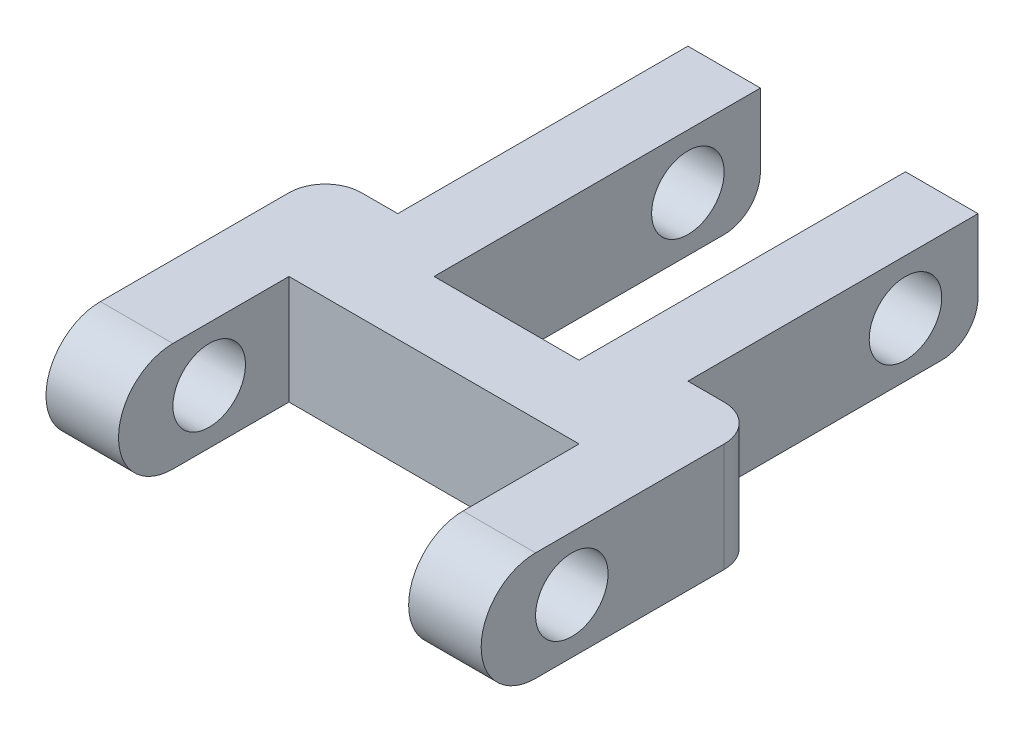
SolidWorks part; units mm, degrees
ref_plane "前视基准面" through (0, 0, 0) normal (0, 0, 1) x (1, 0, 0)
ref_plane "上视基准面" through (0, 0, 0) normal (0, 1, 0) x (1, 0, 0)
ref_plane "右视基准面" through (0, 0, 0) normal (1, 0, 0) x (0, 0, -1)
other "Configuration Table"
sketch "草图1" plane through (0, 0, 0) normal (0, 1, 0) x (1, 0, 0)
  line L0 (-6, 0) -> (6, 0)
  line L1 (-6, 0) -> (-6, -8.7)
  line L2 (-6, -8.7) -> (-4, -8.7)
  line L3 (-4, -8.7) -> (-4, -3)
  line L4 (-4, -3) -> (4, -3)
  line L5 (4, -3) -> (4, -8.7)
  line L6 (4, -8.7) -> (6, -8.7)
  line L7 (6, -8.7) -> (6, 0)
  point P4 (0, 0)
  dimension "D1" = 8.7
  dimension "D2" = 2
  dimension "D3" = 5.7
  dimension "D4" = 8
  dimension "D5" = 8.7
  dimension "D6" = 5.7
  dimension "D7" = 90
  dimension "D8" = 6
extrude "凸台-拉伸1" add sketch "草图1" along normal blind 3
sketch "草图2" plane through (-6, 0, 0) normal (-1, 0, 0) x (0, 0, 1)
  line L2 (6.2, 3) -> (0, 3)
  line L3 (0, 3) -> (0, 0)
  line L4 (0, 0) -> (6.2, 0)
  arc A0 (6.2, 0) -> (6.2, 3) centre (6.2, 1.5) ccw
  dimension "D2" = 6.2
  dimension "D1" = 1.5
  dimension "D3" = 1.5
  dimension "D4" = 6.2
  dimension "D5" = 1.5
extrude "切除-拉伸1" cut sketch "草图2" against normal blind 12 flip side to cut
sketch "草图3" plane through (-6, 0, 0) normal (-1, 0, 0) x (0, 0, 1)
  line L0 (6.2, 1.5) -> (5.2, 1.5) construction
  circle A2 centre (5.2, 1.5) radius 1
  dimension "D3" = 2
  dimension "D2" = 1
extrude "切除-拉伸2" cut sketch "草图3" against normal blind 12
fillet "圆角1" radius 1 2 edges at (6, 1.5, 0) (-6, 1.5, 0)
sketch "草图4" plane through (0, 0, 0) normal (0, 0, -1) x (-1, 0, 0)
  line L0 (0, 3) -> (0, 0) construction
  line L1 (-5, 3) -> (5, 3) construction
  circle A0 centre (0, 1.5) radius 0.95
  dimension "D1" = 1.9
extrude "凸台-拉伸2" add sketch "草图4" along normal blind 2
ref_plane "基准面1" through (0, 0, -2) normal (0, 0, -1) x (-1, 0, 0)
sketch "草图5" plane through (0, 0, -2) normal (0, 0, -1) x (-1, 0, 0)
  line L15 (-4, 3) -> (4, 3)
  line L16 (-5, 3) -> (5, 3) construction
  line L17 (4, 3) -> (4, 0)
  line L18 (-5, 0) -> (5, 0) construction
  line L19 (4, 0) -> (-4, 0)
  line L20 (-4, 0) -> (-4, 3)
  point P5 (0, 3)
  dimension "D1" = 3
  dimension "D2" = 8
extrude "凸台-拉伸3" add sketch "草图5" along normal blind 6
sketch "草图6" plane through (4, 0, 0) normal (1, 0, 0) x (0, 0, -1)
  line L0 (8, 1.5) -> (6, 1.5) construction
  line L1 (8, 3) -> (8, 0) construction
  circle A1 centre (6, 1.5) radius 1
  dimension "D3" = 2
  dimension "D1" = 2
extrude "切除-拉伸3" cut sketch "草图6" against normal blind 12
sketch "草图8" plane through (0, 3, 0) normal (0, 1, 0) x (1, 0, 0)
  line L0 (-2, 10) -> (2, 8)
  line L1 (-4, 8) -> (4, 8) construction
  line L15 (2, 8) -> (2, 3)
  line L16 (2, 3) -> (-2, 3)
  line L17 (-2, 3) -> (-2, 10)
  point P5 (0, 9)
  dimension "D1" = 5
  dimension "D2" = 7
  dimension "D3" = 2
  dimension "D4" = 2
extrude "切除-拉伸4" cut sketch "草图8" against normal blind 8
sketch "草图9" plane through (0, 3, 0) normal (0, 1, 0) x (1, 0, 0)
  line L0 (-6, 10) -> (-6, 7)
  line L3 (-6, 7) -> (-4, 7)
  line L5 (-4, 7) -> (-4, 10)
  line L6 (-4, 10) -> (-6, 10)
  dimension "D1" = 3
  dimension "D2" = 4
  dimension "D3" = 2
  dimension "D4" = 6
  dimension "D5" = 10
fillet "圆角2" radius 1 2 edges at (3, 0, -8) (-3, 0, -8)
sketch "草图11" plane through (0, 0, -2) normal (0, 0, 1) x (1, 0, 0)
  line L0 (-4, 0) -> (-4, 3)
  line L1 (-4, 3) -> (4, 3)
  line L2 (4, 3) -> (4, 0)
  line L3 (4, 0) -> (-4, 0)
  dimension "D1" = 4
extrude "凸台-拉伸4" add sketch "草图11" along normal up to surface (2 mm away) up to face at (0.95, 1.5, 0)
sketch "草图12" plane through (0, 3, 0) normal (0, 1, 0) x (1, 0, 0)
  line L3 (2, 3) -> (-2, 3)
  line L4 (-2, 3) -> (-2, -1)
  line L5 (-2, -1) -> (2, -1)
  line L6 (2, -1) -> (2, 3)
  line L7 (-2, 8) -> (-2, 3) construction
  line L8 (2, 3) -> (2, 8) construction
  line L9 (-2, 3) -> (2, 3) construction
  dimension "D1" = 4
extrude "切除-拉伸5" cut sketch "草图12" against normal blind 10
